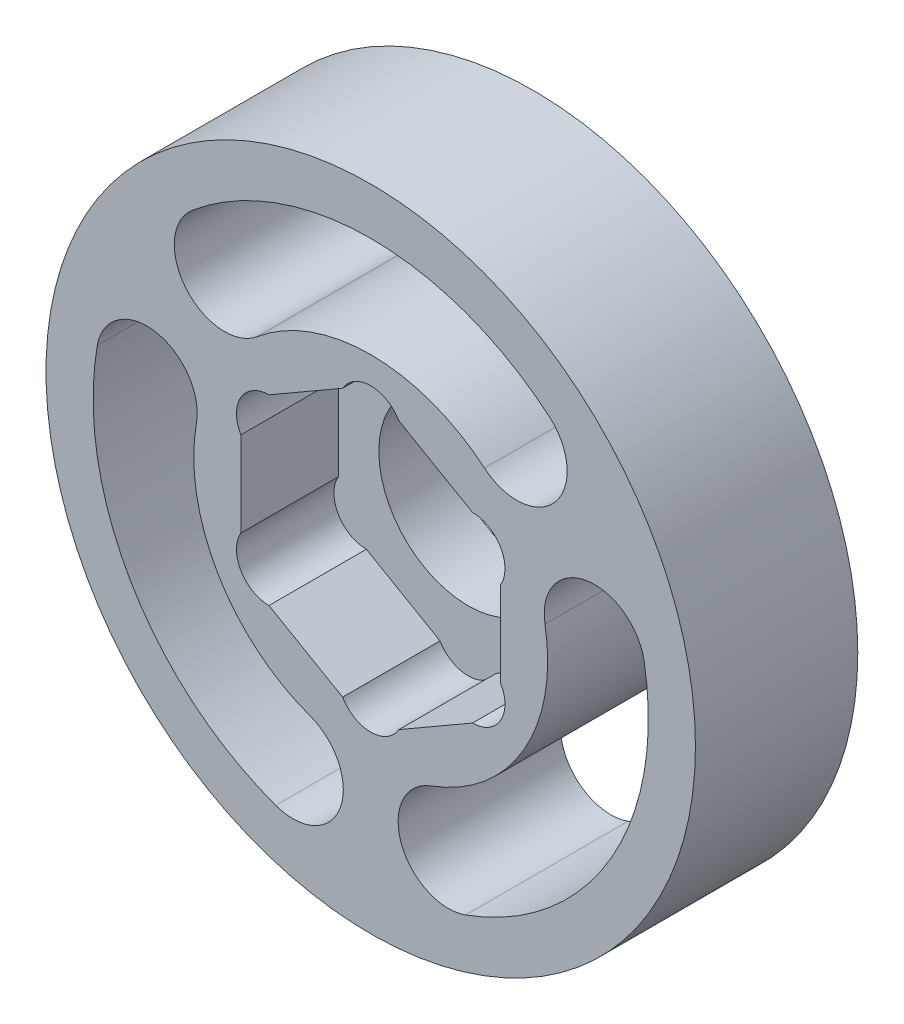
SolidWorks part; units mm, degrees
ref_plane "정면" through (0, 0, 0) normal (0, 0, 1) x (1, 0, 0)
ref_plane "윗면" through (0, 0, 0) normal (0, 1, 0) x (1, 0, 0)
ref_plane "우측면" through (0, 0, 0) normal (1, 0, 0) x (0, 0, -1)
sketch "스케치1" plane through (0, 0, 0) normal (0, 0, 1) x (1, 0, 0)
  circle A0 centre (0, 0) radius 10
  dimension "D1" = 20
extrude "보스-돌출1" add sketch "스케치1" along normal blind 5
sketch "스케치2" plane through (0, 0, 5) normal (0, 0, 1) x (1, 0, 0)
  line L1 (0, 4.6188) -> (-4, 2.3094)
  line L2 (-4, 2.3094) -> (-4, -2.3094)
  line L3 (-4, -2.3094) -> (0, -4.6188)
  line L4 (0, -4.6188) -> (4, -2.3094)
  line L5 (4, -2.3094) -> (4, 2.3094)
  line L6 (4, 2.3094) -> (0, 4.6188)
  circle A0 centre (0, 0) radius 4 construction
  dimension "D1" = 8
extrude "컷-돌출1" cut sketch "스케치2" against normal blind 3
sketch "스케치4" plane through (0, 0, 5) normal (0, 0, 1) x (1, 0, 0)
  line L0 (0, 0) -> (0, 3.6188) construction
  circle A0 centre (0, 3.6188) radius 1
  circle A1 centre (3.134, 1.8094) radius 1
  circle A2 centre (3.134, -1.8094) radius 1
  circle A3 centre (0, -3.6188) radius 1
  circle A4 centre (-3.134, -1.8094) radius 1
  circle A5 centre (-3.134, 1.8094) radius 1
  point P18 (0, 0)
  dimension "D1" = 2
  dimension "D2" = 6
extrude "컷-돌출3" cut sketch "스케치4" against normal blind 3
sketch "스케치3" plane through (0, 0, 5) normal (0, 0, 1) x (1, 0, 0)
  line L0 (4.4995, 5.3623) -> (0, 0) construction
  line L1 (0, 0) -> (0, 7) construction
  line L2 (-4.4995, 5.3623) -> (0, 0) construction
  line L3 (2.3941, -6.5778) -> (0, 0) construction
  line L4 (0, 0) -> (6.0622, -3.5) construction
  line L5 (6.8937, 1.2155) -> (0, 0) construction
  line L6 (-6.8937, 1.2155) -> (0, 0) construction
  line L7 (0, 0) -> (-6.0622, -3.5) construction
  line L8 (-2.3941, -6.5778) -> (0, 0) construction
  arc A0 (4.4995, 5.3623) -> (-4.4995, 5.3623) centre (0, 0) ccw construction
  arc A1 (5.4958, 6.5497) -> (-5.4958, 6.5497) centre (0, 0) ccw
  arc A2 (3.5032, 4.1749) -> (-3.5032, 4.1749) centre (0, 0) ccw
  arc A3 (3.5032, 4.1749) -> (5.4958, 6.5497) centre (4.4995, 5.3623) ccw
  arc A4 (-5.4958, 6.5497) -> (-3.5032, 4.1749) centre (-4.4995, 5.3623) ccw
  arc A5 (2.3941, -6.5778) -> (6.8937, 1.2155) centre (0, 0) ccw construction
  arc A6 (2.9243, -8.0344) -> (8.4201, 1.4847) centre (0, 0) ccw
  arc A7 (1.864, -5.1213) -> (5.3672, 0.9464) centre (0, 0) ccw
  arc A8 (1.864, -5.1213) -> (2.9243, -8.0344) centre (2.3941, -6.5778) ccw
  arc A9 (8.4201, 1.4847) -> (5.3672, 0.9464) centre (6.8937, 1.2155) ccw
  arc A10 (-6.8937, 1.2155) -> (-2.3941, -6.5778) centre (0, 0) ccw construction
  arc A11 (-8.4201, 1.4847) -> (-2.9243, -8.0344) centre (0, 0) ccw
  arc A12 (-5.3672, 0.9464) -> (-1.864, -5.1213) centre (0, 0) ccw
  arc A13 (-5.3672, 0.9464) -> (-8.4201, 1.4847) centre (-6.8937, 1.2155) ccw
  arc A14 (-2.9243, -8.0344) -> (-1.864, -5.1213) centre (-2.3941, -6.5778) ccw
  point P4 (0, 7)
  point P18 (6.0622, -3.5)
  point P28 (-6.0622, -3.5)
  point P36 (0, 0)
  dimension "D3" = 1.55
  dimension "D1" = 80
  dimension "D2" = 7
  dimension "D4" = 3
extrude "컷-돌출2" cut sketch "스케치3" against normal blind 5
sketch "스케치5" plane through (0, 0, 0) normal (0, 0, -1) x (-1, 0, 0)
  circle A0 centre (0, 0) radius 2.75
  dimension "D1" = 5.5
extrude "컷-돌출4" cut sketch "스케치5" against normal blind 10
